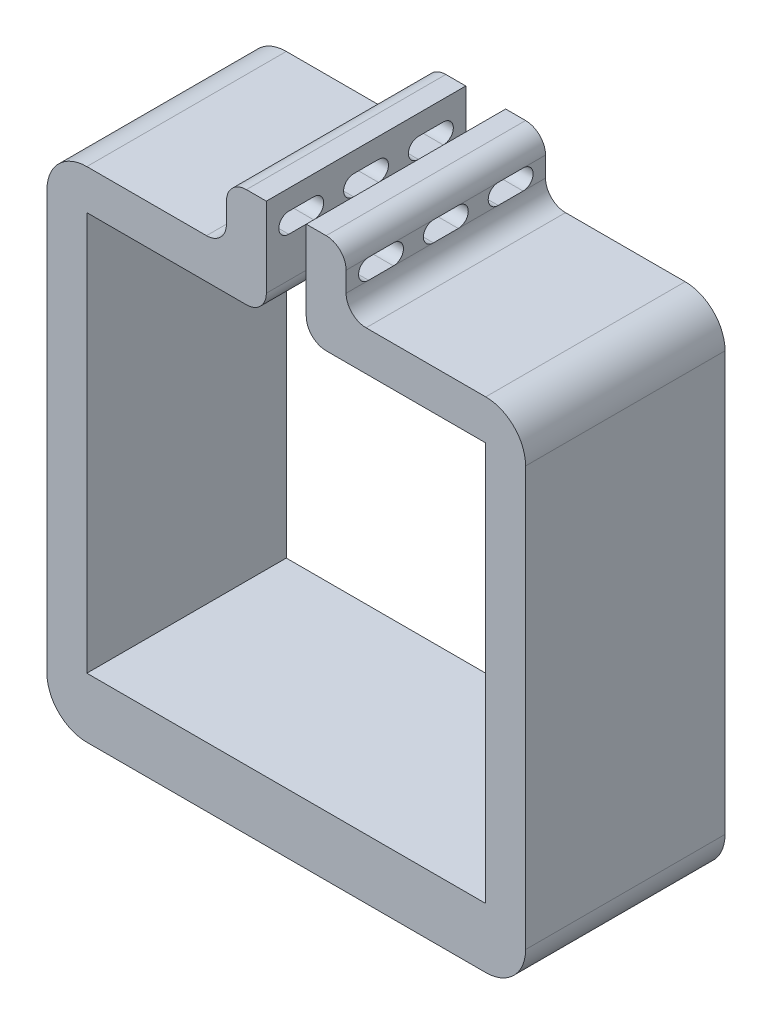
SolidWorks part; units mm, degrees
ref_plane "Front Plane" through (0, 0, 0) normal (0, 0, 1) x (1, 0, 0)
ref_plane "Top Plane" through (0, 0, 0) normal (0, 1, 0) x (1, 0, 0)
ref_plane "Right Plane" through (0, 0, 0) normal (1, 0, 0) x (0, 0, -1)
sketch "Sketch1" plane through (0, 0, 0) normal (0, 0, 1) x (1, 0, 0)
  line L1 (0, 0) -> (50.8, 0)
  line L2 (0, 0) -> (0, 50.8)
  line L3 (0, 50.8) -> (50.8, 50.8)
  line L4 (50.8, 0) -> (50.8, 50.8)
  line L5 (0, 55.88) -> (50.8, 55.88)
  line L8 (-5.08, -5.08) -> (55.88, -5.08) construction
  line L9 (55.88, -5.08) -> (55.88, 55.88) construction
  line L10 (-5.08, 55.88) -> (55.88, 55.88) construction
  line L11 (-5.08, -5.08) -> (-5.08, 55.88) construction
  line L12 (-5.08, 50.8) -> (-5.08, -2.54)
  line L13 (0, -7.62) -> (50.8, -7.62)
  line L14 (55.88, -2.54) -> (55.88, 50.8)
  arc A0 (50.8, -7.62) -> (55.88, -2.54) centre (50.8, -2.54) ccw
  arc A1 (55.88, 50.8) -> (50.8, 55.88) centre (50.8, 50.8) ccw
  arc A2 (0, 55.88) -> (-5.08, 50.8) centre (0, 50.8) ccw
  arc A3 (0, -7.62) -> (-5.08, -2.54) centre (0, -2.54) cw
  point P21 (0, 0)
  point P22 (0, 0)
  point P23 (0, 0)
  point P24 (0, 0)
  point P25 (0, 0)
  point P26 (0, 0)
  dimension "D4" = 5.08
  dimension "D1" = 50.8
  dimension "D2" = 50.8
  dimension "D3" = 5.08
  dimension "D5" = 5.08
  dimension "D6" = 7.62
  dimension "D7" = 5.08
extrude "Boss-Extrude1" add sketch "Sketch1" along normal blind 25.4
sketch "Sketch2" plane through (0, 0, 25.4) normal (0, 0, 1) x (1, 0, 0)
  line L0 (50.8, 50.8) -> (0, 50.8) construction
  line L6 (22.86, 53.34) -> (-4.3994, 53.34) construction
  line L7 (27.94, 53.34) -> (55.1994, 53.34) construction
  line L8 (50.8, 55.88) -> (0, 55.88) construction
  line L9 (22.86, 55.88) -> (27.94, 55.88)
  line L10 (22.86, 55.88) -> (22.86, 50.8)
  line L11 (22.86, 50.8) -> (27.94, 50.8)
  line L12 (27.94, 55.88) -> (27.94, 50.8)
  arc A0 (0, 55.88) -> (-5.08, 50.8) centre (0, 50.8) ccw construction
  arc A1 (55.88, 50.8) -> (50.8, 55.88) centre (50.8, 50.8) ccw construction
  dimension "D1" = 5.08
extrude "Cut-Extrude1" cut sketch "Sketch2" against normal through all
fillet "Fillet1" radius 2.54 2 edges at (27.94, 50.8, 12.7) (22.86, 50.8, 12.7)
sketch "Sketch3" plane through (0, 0, 25.4) normal (0, 0, 1) x (1, 0, 0)
  line L1 (22.86, 55.88) -> (17.78, 55.88)
  line L2 (22.86, 55.88) -> (22.86, 63.5)
  line L3 (22.86, 63.5) -> (17.78, 63.5)
  line L4 (17.78, 55.88) -> (17.78, 63.5)
  line L5 (27.94, 55.88) -> (33.02, 55.88)
  line L6 (27.94, 55.88) -> (27.94, 63.5)
  line L7 (27.94, 63.5) -> (33.02, 63.5)
  line L8 (33.02, 55.88) -> (33.02, 63.5)
  dimension "D1" = 5.08
  dimension "D2" = 5.08
  dimension "D3" = 7.62
extrude "Boss-Extrude2" add sketch "Sketch3" against normal up to surface (25.4 mm away) up to face at (25.4, 34.0904, 0)
fillet "Fillet2" radius 2.54 4 edges at (33.02, 55.88, 12.7) (17.78, 55.88, 12.7) (33.02, 63.5, 12.7) (17.78, 63.5, 12.7)
sketch "Sketch4" plane through (17.78, 0, 0) normal (-1, 0, 0) x (0, 0, 1)
  line L0 (2.8575, 59.69) -> (6.0325, 59.69) construction
  line L1 (2.8575, 60.96) -> (6.0325, 60.96)
  line L2 (2.8575, 58.42) -> (6.0325, 58.42)
  line L3 (11.1125, 59.69) -> (14.2875, 59.69) construction
  line L4 (11.1125, 60.96) -> (14.2875, 60.96)
  line L5 (11.1125, 58.42) -> (14.2875, 58.42)
  line L6 (19.3675, 59.69) -> (22.5425, 59.69) construction
  line L7 (19.3675, 60.96) -> (22.5425, 60.96)
  line L8 (19.3675, 58.42) -> (22.5425, 58.42)
  line L9 (6.0325, 59.69) -> (11.1125, 59.69) construction
  line L10 (14.2875, 59.69) -> (19.3675, 59.69) construction
  line L11 (2.8575, 59.69) -> (0, 59.69) construction
  line L12 (0, 58.42) -> (0, 60.96) construction
  line L13 (22.5425, 59.69) -> (25.4, 59.69) construction
  line L14 (25.4, 60.96) -> (25.4, 58.42) construction
  arc A0 (2.8575, 60.96) -> (2.8575, 58.42) centre (2.8575, 59.69) ccw
  arc A1 (6.0325, 58.42) -> (6.0325, 60.96) centre (6.0325, 59.69) ccw
  arc A2 (11.1125, 60.96) -> (11.1125, 58.42) centre (11.1125, 59.69) ccw
  arc A3 (14.2875, 58.42) -> (14.2875, 60.96) centre (14.2875, 59.69) ccw
  arc A4 (19.3675, 60.96) -> (19.3675, 58.42) centre (19.3675, 59.69) ccw
  arc A5 (22.5425, 58.42) -> (22.5425, 60.96) centre (22.5425, 59.69) ccw
  point P2 (4.445, 59.69)
  point P9 (12.7, 59.69)
  point P14 (20.955, 59.69)
  dimension "D5" = 1.27
  dimension "D1" = 3.175
  dimension "D2" = 3.175
  dimension "D3" = 3.175
  dimension "D4" = 5.08
extrude "Cut-Extrude2" cut sketch "Sketch4" against normal through all
